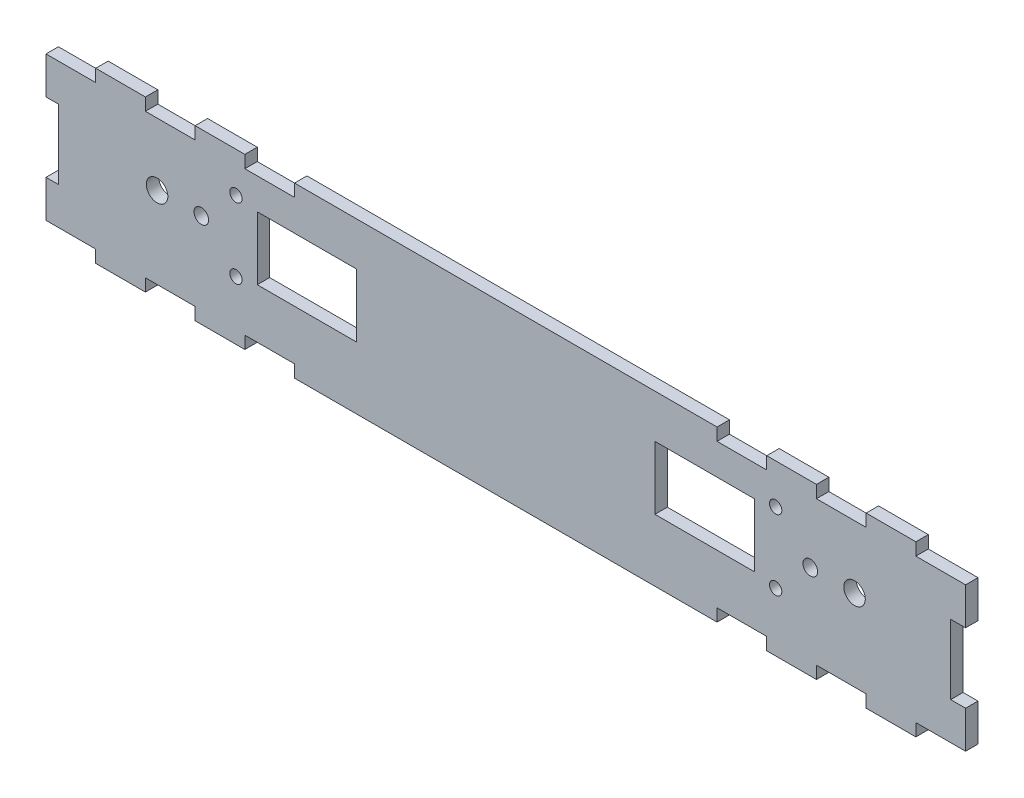
SolidWorks part; units mm, degrees
material "Acrylic (Medium-high impact)"
ref_plane "Front Plane" through (0, 0, 0) normal (0, 0, 1) x (1, 0, 0)
ref_plane "Top Plane" through (0, 0, 0) normal (0, 1, 0) x (1, 0, 0)
ref_plane "Right Plane" through (0, 0, 0) normal (1, 0, 0) x (0, 0, -1)
sketch "Sketch3" plane through (0, 0, 0) normal (0, 0, 1) x (1, 0, 0)
  line L0 (0, 22.5) -> (0, 0)
  line L1 (0, 0) -> (31.6, 0)
  line L2 (36.6, 5) -> (36.6, 17.5)
  line L3 (31.6, 22.5) -> (0, 22.5)
  line L4 (0, 0) -> (-63.5, 0) construction
  line L5 (-63.5, 0) -> (-63.5, 28.85) construction
  line L6 (-158.6, 22.5) -> (-127, 22.5)
  line L7 (0, 22.5) -> (-25.4, 22.5)
  line L8 (0, 22.5) -> (0, 0)
  line L9 (0, 0) -> (-25.4, 0)
  line L10 (-25.4, 22.5) -> (-25.4, 0)
  line L11 (-163.6, 5) -> (-163.6, 17.5)
  line L12 (-127, 0) -> (-158.6, 0)
  line L13 (-127, 22.5) -> (-127, 0)
  line L14 (-127, 0) -> (-101.6, 0)
  line L15 (-101.6, 22.5) -> (-101.6, 0)
  line L16 (-127, 22.5) -> (-101.6, 22.5)
  line L17 (-127, 22.5) -> (-127, 0)
  line L18 (-180.975, 28.85) -> (-180.975, -6.3925)
  line L21 (20.8125, -11.155) -> (58.7375, -11.155)
  line L22 (58.7375, 0) -> (58.7375, -11.155)
  line L25 (-179.3875, 28.85) -> (-185.7375, 28.85)
  line L26 (-185.7375, 22.5) -> (-185.7375, 28.85)
  line L27 (-185.7375, 28.85) -> (58.7375, 28.85)
  line L28 (-185.7375, 28.85) -> (-185.7375, -11.155)
  line L29 (-185.7375, -11.155) -> (58.7375, -11.155)
  line L30 (58.7375, 28.85) -> (58.7375, -11.155)
  line L31 (-180.975, -6.3925) -> (58.7375, -6.3925)
  line L32 (-185.7375, 24.0875) -> (53.975, 24.0875)
  line L33 (53.975, 24.0875) -> (53.975, -11.155)
  line L35 (-127, 22.5) -> (-101.6, 22.5)
  line L36 (-127, 22.5) -> (-127, 19.325)
  line L37 (-127, 19.325) -> (-101.6, 19.325)
  line L38 (-101.6, 22.5) -> (-101.6, 19.325)
  line L39 (-127, 0) -> (-101.6, 0)
  line L40 (-127, 0) -> (-127, 3.175)
  line L41 (-127, 3.175) -> (-101.6, 3.175)
  line L42 (-101.6, 0) -> (-101.6, 3.175)
  line L43 (0, 22.5) -> (-25.4, 22.5)
  line L44 (0, 22.5) -> (0, 19.325)
  line L45 (0, 19.325) -> (-25.4, 19.325)
  line L46 (-25.4, 22.5) -> (-25.4, 19.325)
  line L47 (0, 0) -> (-25.4, 0)
  line L48 (0, 0) -> (0, 3.175)
  line L49 (0, 3.175) -> (-25.4, 3.175)
  line L50 (-25.4, 0) -> (-25.4, 3.175)
  circle A2 centre (5.45, 2.25) radius 1.575
  circle A3 centre (5.45, 20.25) radius 1.575
  arc A6 (31.6, 0) -> (36.6, 5) centre (31.6, 5) ccw
  arc A7 (36.6, 17.5) -> (31.6, 22.5) centre (31.6, 17.5) ccw
  arc A8 (22.85, 11.25) -> (28.35, 11.25) centre (25.6, 11.25) ccw
  arc A9 (28.35, 11.25) -> (22.85, 11.25) centre (25.6, 11.25) ccw
  arc A10 (12.425, 11.25) -> (16.175, 11.25) centre (14.3, 11.25) ccw
  arc A11 (16.175, 11.25) -> (12.425, 11.25) centre (14.3, 11.25) ccw
  arc A12 (-143.175, 11.25) -> (-139.425, 11.25) centre (-141.3, 11.25) cw
  arc A13 (-139.425, 11.25) -> (-143.175, 11.25) centre (-141.3, 11.25) cw
  arc A14 (-155.35, 11.25) -> (-149.85, 11.25) centre (-152.6, 11.25) cw
  arc A15 (-149.85, 11.25) -> (-155.35, 11.25) centre (-152.6, 11.25) cw
  arc A16 (-163.6, 17.5) -> (-158.6, 22.5) centre (-158.6, 17.5) cw
  arc A17 (-158.6, 0) -> (-163.6, 5) centre (-158.6, 5) cw
  circle A18 centre (-132.45, 20.25) radius 1.575
  circle A19 centre (-132.45, 2.25) radius 1.575
  dimension "D3" = 5.45
  dimension "D4" = 3.15
  dimension "D8" = 3.15
  dimension "D6" = 2.25
  dimension "D9" = 1.875
  dimension "D10" = 4.7625
  dimension "D11" = 2.75
  dimension "D12" = 4.7625
  dimension "D17" = 5
  dimension "D18" = 5
  dimension "D1" = 31.6
  dimension "D2" = 36.6
  dimension "D5" = 2.25
  dimension "D7" = 5.45
  dimension "D13" = 11.25
  dimension "D14" = 14.3
  dimension "D15" = 11
  dimension "D16" = 11.25
  dimension "D19" = 22.5
  dimension "D20" = 244.475
  dimension "D21" = 30.48
  dimension "D22" = 25.4
  dimension "D23" = 3.175
  dimension "D24" = 25.4
  dimension "D25" = 3.175
  dimension "D26" = 25.4
extrude "Boss-Extrude1" add sketch "Sketch3" along normal blind 3.175 contours L33 L32 L18 L31 A7 L2 A6 L1 L9 L10 L7 L3 L12 A17 L11 A16 L6 L16 L15 L14 | A17 L12 L13 L6 A16 L11 A18 A12 A13 A14 A15 A19 | L2 A7 L3 L0 L1 A6 A11 A10 A9 A8 A2 A3 | L0 L49 L10 L9 | L45 L0 L7 L10 | L13 L37 L15 L16 | L40 L41 L42 L39
sketch "Sketch4" plane through (0, 0, 3.175) normal (0, 0, 1) x (1, 0, 0)
  line L0 (-155.575, 30.4375) -> (-155.575, 27.2625)
  line L1 (-180.975, 24.0875) -> (53.975, 24.0875)
  line L2 (-180.975, 24.0875) -> (-180.975, 30.4375)
  line L3 (-180.975, 30.4375) -> (53.975, 30.4375)
  line L4 (53.975, -6.3925) -> (53.975, 24.0875)
  line L5 (53.975, 24.0875) -> (-180.975, 24.0875)
  line L6 (-180.975, 24.0875) -> (-180.975, -6.3925)
  line L7 (-180.975, -6.3925) -> (53.975, -6.3925)
  line L8 (53.975, -6.3925) -> (53.975, 24.0875)
  line L9 (53.975, 24.0875) -> (-180.975, 24.0875)
  line L10 (-180.975, 24.0875) -> (-180.975, -6.3925)
  line L11 (-180.975, -6.3925) -> (53.975, -6.3925)
  line L12 (53.975, 24.0875) -> (53.975, 30.4375)
  line L13 (-180.975, 30.4375) -> (53.975, 30.4375)
  line L14 (-180.975, 30.4375) -> (-180.975, 27.2625)
  line L15 (-180.975, 27.2625) -> (53.975, 27.2625)
  line L16 (53.975, 30.4375) -> (53.975, 27.2625)
  line L17 (-180.975, 30.4375) -> (-168.275, 30.4375)
  line L18 (-180.975, 30.4375) -> (-180.975, 27.2625)
  line L19 (-180.975, 27.2625) -> (-168.275, 27.2625)
  line L20 (-168.275, 30.4375) -> (-168.275, 27.2625)
  line L21 (-155.575, 30.4375) -> (-142.875, 30.4375)
  line L22 (-142.875, 30.4375) -> (-142.875, 27.2625)
  line L23 (-155.575, 27.2625) -> (-142.875, 27.2625)
  line L24 (-130.175, 30.4375) -> (-130.175, 27.2625)
  line L25 (-130.175, 30.4375) -> (-117.475, 30.4375)
  line L26 (-117.475, 30.4375) -> (-117.475, 27.2625)
  line L27 (-130.175, 27.2625) -> (-117.475, 27.2625)
  line L28 (28.575, 27.2625) -> (28.575, 30.4375)
  line L29 (53.975, 27.2625) -> (41.275, 27.2625)
  line L30 (53.975, 27.2625) -> (53.975, 30.4375)
  line L31 (53.975, 30.4375) -> (41.275, 30.4375)
  line L32 (41.275, 27.2625) -> (41.275, 30.4375)
  line L33 (28.575, 27.2625) -> (15.875, 27.2625)
  line L34 (15.875, 27.2625) -> (15.875, 30.4375)
  line L35 (28.575, 30.4375) -> (15.875, 30.4375)
  line L36 (3.175, 27.2625) -> (3.175, 30.4375)
  line L37 (3.175, 27.2625) -> (-9.525, 27.2625)
  line L38 (-9.525, 27.2625) -> (-9.525, 30.4375)
  line L39 (3.175, 30.4375) -> (-9.525, 30.4375)
  line L40 (-180.975, 8.8475) -> (49.4654, 8.8475) construction
  line L41 (3.175, -12.7425) -> (-9.525, -12.7425)
  line L42 (-9.525, -9.5675) -> (-9.525, -12.7425)
  line L43 (3.175, -9.5675) -> (-9.525, -9.5675)
  line L44 (3.175, -9.5675) -> (3.175, -12.7425)
  line L45 (28.575, -12.7425) -> (15.875, -12.7425)
  line L46 (15.875, -9.5675) -> (15.875, -12.7425)
  line L47 (28.575, -9.5675) -> (15.875, -9.5675)
  line L48 (41.275, -9.5675) -> (41.275, -12.7425)
  line L49 (53.975, -12.7425) -> (41.275, -12.7425)
  line L50 (53.975, -9.5675) -> (53.975, -12.7425)
  line L51 (53.975, -9.5675) -> (41.275, -9.5675)
  line L52 (28.575, -9.5675) -> (28.575, -12.7425)
  line L53 (-130.175, -9.5675) -> (-117.475, -9.5675)
  line L54 (-117.475, -12.7425) -> (-117.475, -9.5675)
  line L55 (-130.175, -12.7425) -> (-117.475, -12.7425)
  line L56 (-130.175, -12.7425) -> (-130.175, -9.5675)
  line L57 (-155.575, -9.5675) -> (-142.875, -9.5675)
  line L58 (-142.875, -12.7425) -> (-142.875, -9.5675)
  line L59 (-155.575, -12.7425) -> (-142.875, -12.7425)
  line L60 (-168.275, -12.7425) -> (-168.275, -9.5675)
  line L61 (-180.975, -9.5675) -> (-168.275, -9.5675)
  line L62 (-180.975, -12.7425) -> (-180.975, -9.5675)
  line L63 (-180.975, -12.7425) -> (-168.275, -12.7425)
  line L64 (53.975, -12.7425) -> (53.975, -9.5675)
  line L65 (-180.975, -9.5675) -> (53.975, -9.5675)
  line L66 (-180.975, -12.7425) -> (-180.975, -9.5675)
  line L67 (-180.975, -12.7425) -> (53.975, -12.7425)
  line L68 (53.975, -6.3925) -> (53.975, -12.7425)
  line L69 (53.975, -6.3925) -> (-180.975, -6.3925)
  line L70 (-180.975, -12.7425) -> (53.975, -12.7425)
  line L71 (-180.975, -6.3925) -> (-180.975, -12.7425)
  line L72 (-180.975, -6.3925) -> (53.975, -6.3925)
  line L73 (-155.575, -12.7425) -> (-155.575, -9.5675)
  line M29 (53.975, 24.0875) -> (-180.975, 24.0875)
  line M31 (-180.975, -6.3925) -> (53.975, -6.3925)
  dimension "D2" = 6.35
  dimension "D3" = 3.175
  dimension "D4" = 12.7
  dimension "D5" = 3
  dimension "D6" = 12.7
  dimension "D7" = 3
  dimension "D1" = 0
extrude "Boss-Extrude2" add sketch "Sketch4" against normal blind 3.175 contours L15 L38 L13 L26 | L24 L13 L22 L15 | L13 L20 L15 L0 | L15 L2 L12 M29 | L36 L15 L34 L3 | L15 L32 L3 L28 | L71 L61 L65 L57 L53 L43 L47 L51 L68 M31 | L52 L67 L48 L65 | L44 L67 L46 L65 | L54 L67 L42 L65 | L58 L67 L56 L65 | L67 L73 L65 L60
sketch "Sketch5" plane through (0, 0, 3.175) normal (0, 0, 1) x (1, 0, 0)
  line L0 (53.975, 27.2625) -> (53.975, -9.5675) construction
  line L1 (-168.275, -12.7425) -> (-180.975, -12.7425)
  line L2 (-168.275, -12.7425) -> (-168.275, -0.0425)
  line L3 (-168.275, -0.0425) -> (-180.975, -0.0425)
  line L4 (-180.975, -12.7425) -> (-180.975, -0.0425)
  line L5 (-180.975, 27.2625) -> (-180.975, -9.5675) construction
  line L6 (-168.275, 30.4375) -> (-180.975, 30.4375)
  line L7 (-168.275, 30.4375) -> (-168.275, 17.7375)
  line L8 (-168.275, 17.7375) -> (-180.975, 17.7375)
  line L9 (-180.975, 30.4375) -> (-180.975, 17.7375)
  line L10 (41.275, 30.4375) -> (53.975, 30.4375)
  line L11 (41.275, 30.4375) -> (41.275, 17.7375)
  line L12 (41.275, 17.7375) -> (53.975, 17.7375)
  line L13 (53.975, 30.4375) -> (53.975, 17.7375)
  line L15 (41.275, -12.7425) -> (53.975, -12.7425)
  line L16 (41.275, -12.7425) -> (41.275, -0.0425)
  line L17 (41.275, -0.0425) -> (53.975, -0.0425)
  line L18 (53.975, -12.7425) -> (53.975, -0.0425)
  line L19 (-180.975, 17.7375) -> (-177.8, 17.7375)
  line L20 (-180.975, 17.7375) -> (-180.975, -0.0425)
  line L21 (-180.975, -0.0425) -> (-177.8, -0.0425)
  line L22 (-177.8, 17.7375) -> (-177.8, -0.0425)
  line L23 (53.975, 17.7375) -> (50.165, 17.7375)
  line L24 (53.975, 17.7375) -> (53.975, -0.0425)
  line L25 (53.975, -0.0425) -> (50.165, -0.0425)
  line L26 (50.165, 17.7375) -> (50.165, -0.0425)
  dimension "D1" = 12.7
  dimension "D2" = 12.7
  dimension "D3" = 12.7
  dimension "D4" = 3.175
  dimension "D5" = 3.81
extrude "Cut-Extrude1" cut sketch "Sketch5" against normal blind 7.62 contours L22 L8 L20 L3 | L12 L26 L17 L24
